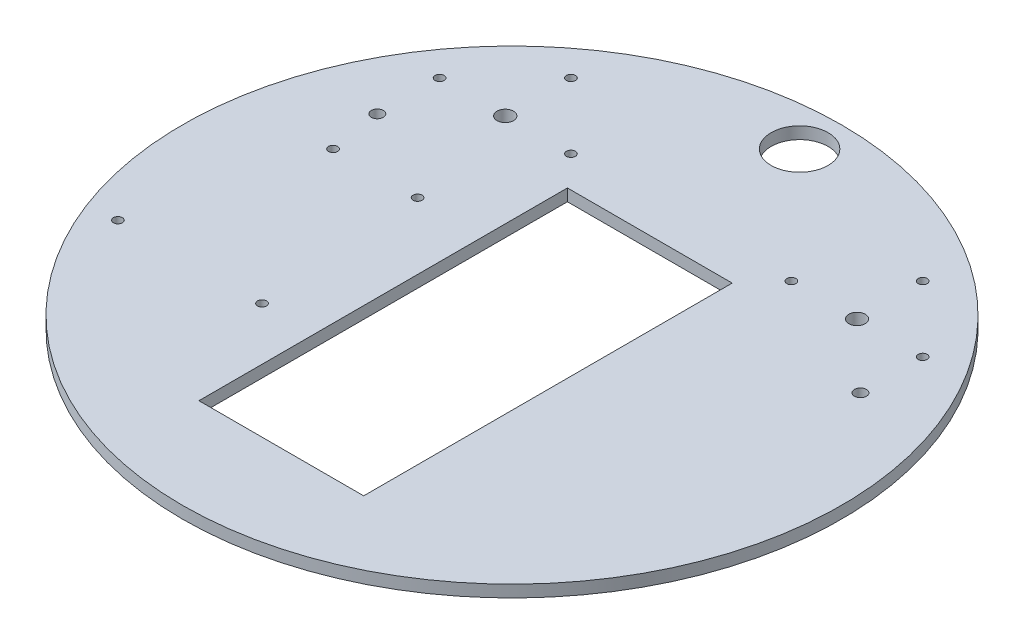
SolidWorks part; units mm, degrees
ref_plane "Front Plane" through (0, 0, 0) normal (0, 0, 1) x (1, 0, 0)
ref_plane "Top Plane" through (0, 0, 0) normal (0, 1, 0) x (1, 0, 0)
ref_plane "Right Plane" through (0, 0, 0) normal (1, 0, 0) x (0, 0, -1)
sketch "Sketch1" plane through (0, 0, 0) normal (0, 1, 0) x (1, 0, 0)
  line L0 (0, -110) -> (0, 110) construction
  line L6 (-110, 0) -> (110, 0) construction
  line L7 (-27.5, -77) -> (27.5, -77)
  line L8 (-27.5, -77) -> (-27.5, 46)
  line L9 (-27.5, 46) -> (27.5, 46)
  line L10 (27.5, -77) -> (27.5, 46)
  line L11 (-27.5, -77) -> (27.5, 46) construction
  line L12 (-27.5, 46) -> (27.5, -77) construction
  circle A0 centre (0, 0) radius 110 construction
  circle A1 centre (0, 96) radius 9.5
  arc A2 (-110, 0) -> (110, 0) centre (0, 0) cw
  arc A3 (-37.5, -103.4106) -> (37.5, -103.4106) centre (0, 0) ccw
  arc A4 (110, 0) -> (37.5, -103.4106) centre (0, 0) cw
  arc A5 (-37.5, -103.4106) -> (-110, 0) centre (0, 0) cw
  point P3 (0, 0)
  point P10 (0, 0)
  point P11 (0, -15.5)
  dimension "D3" = 19
  dimension "D5" = 14
  dimension "D2" = 110
  dimension "D1" = 55
  dimension "D4" = 33
  dimension "D6" = 50
extrude "fond" add sketch "Sketch1" along normal blind 4
sketch "Sketch5" plane through (0, 4, 0) normal (0, 1, 0) x (1, 0, 0)
  line L0 (0, 110) -> (0, -110) construction
  line L1 (58.7078, 78.3764) -> (36.7875, 56.4561) construction
  line L2 (58.7078, 78.3764) -> (80.6281, 56.4561) construction
  line L3 (36.7875, 56.4561) -> (58.7078, 34.5358) construction
  line L4 (80.6281, 56.4561) -> (58.7078, 34.5358) construction
  line L5 (58.7078, 78.3764) -> (58.7078, 34.5358) construction
  line L6 (36.7875, 56.4561) -> (80.6281, 56.4561) construction
  line L7 (-36.7875, 56.4561) -> (-80.6281, 56.4561) construction
  line L8 (-58.7078, 78.3764) -> (-58.7078, 34.5358) construction
  line L9 (-80.6281, 56.4561) -> (-58.7078, 34.5358) construction
  line L10 (-36.7875, 56.4561) -> (-58.7078, 34.5358) construction
  line L11 (-58.7078, 78.3764) -> (-80.6281, 56.4561) construction
  line L12 (-58.7078, 78.3764) -> (-36.7875, 56.4561) construction
  circle A0 centre (0, 0) radius 110 construction
  circle A1 centre (36.7875, 56.4561) radius 1.5
  circle A2 centre (58.7078, 78.3764) radius 1.5
  circle A3 centre (80.6281, 56.4561) radius 1.5
  circle A4 centre (-80.6281, 56.4561) radius 1.5
  circle A5 centre (-58.7078, 78.3764) radius 1.5
  circle A6 centre (-36.7875, 56.4561) radius 1.5
  circle A7 centre (58.7078, 56.4561) radius 2.75
  circle A8 centre (-58.7078, 56.4561) radius 2.75
  point P6 (58.7078, 56.4561)
  point P20 (-58.7078, 56.4561)
  dimension "D2" = 3
  dimension "D3" = 5.5
  dimension "D1" = 31
extrude "trous steppers" cut sketch "Sketch5" against normal up to next and the other way through all
sketch "Sketch7" plane through (0, 4, 0) normal (0, 1, 0) x (1, 0, 0)
  line L1 (0, 0) -> (0, 31.1428) construction
  circle A0 centre (80.6281, 35.6755) radius 2
  circle A1 centre (-80.6281, 35.6755) radius 2
  point P0 (80.6281, 56.4561)
  dimension "D1" = 4
extrude "trous poulies" cut sketch "Sketch7" against normal up to next
sketch "Sketch9" plane through (0, 4, 0) normal (0, 1, 0) x (1, 0, 0)
  line L0 (-95.8872, 18.1644) -> (-82.3872, 18.1644) construction
  line L1 (-95.8872, -47.7356) -> (-42.3872, -47.7356) construction
  line L2 (-95.8872, -47.7356) -> (-95.8872, 18.1644) construction
  line L3 (-95.8872, 18.1644) -> (-42.3872, 18.1644) construction
  line L4 (-42.3872, -47.7356) -> (-42.3872, 18.1644) construction
  line L5 (-95.8872, -47.7356) -> (-42.3872, 18.1644) construction
  line L6 (-95.8872, 18.1644) -> (-42.3872, -47.7356) construction
  line L7 (-82.3872, 18.1644) -> (-79.7322, 20.9244) construction
  line L8 (-79.7322, 20.9244) -> (-47.0422, 20.9244) construction
  line L9 (-95.8872, -38.3505) -> (-42.3872, -38.3505) construction
  line L10 (-47.0422, 20.9244) -> (-44.3872, 18.1644) construction
  line L11 (-44.3872, 18.1644) -> (-42.3872, 18.1644) construction
  circle A0 centre (-49.6872, 18.1644) radius 1.5
  circle A1 centre (-77.8872, 18.1644) radius 1.5
  circle A2 centre (-93.1872, -38.3505) radius 1.5
  circle A3 centre (-45.0872, -38.3505) radius 1.5
  point P0 (-69.1372, -14.7856)
  dimension "D14" = 3
  dimension "D1" = 65.9
  dimension "D2" = 53.5
  dimension "D3" = 32.69
  dimension "D4" = 40
  dimension "D5" = 68.66
  dimension "D6" = 7.3
  dimension "D7" = 2
  dimension "D8" = 18
  dimension "D9" = 2.7
  dimension "D10" = 2.7
  dimension "D11" = 9.3851
extrude "trous carte" cut sketch "Sketch9" against normal up to next
